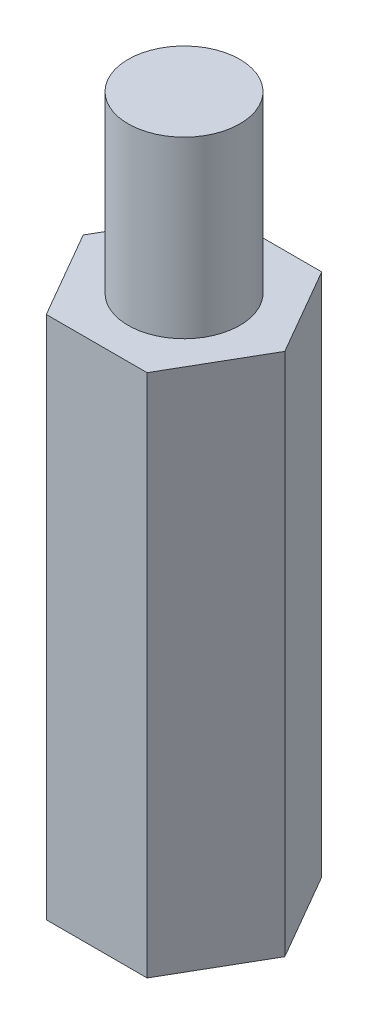
SolidWorks part; units mm, degrees
ref_plane "Front Plane" through (0, 0, 0) normal (0, 0, 1) x (1, 0, 0)
ref_plane "Top Plane" through (0, 0, 0) normal (0, 1, 0) x (1, 0, 0)
ref_plane "Right Plane" through (0, 0, 0) normal (1, 0, 0) x (0, 0, -1)
sketch "Sketch1" plane through (0, 0, 0) normal (0, 1, 0) x (1, 0, 0)
  line L0 (0, 52.3008) -> (0, -73.4946) construction
  line L1 (-96.1697, 0) -> (114.4009, 0) construction
  line L2 (-1.3748, 2.3812) -> (1.3748, 2.3812)
  line L3 (1.3748, 2.3812) -> (2.7496, 0)
  line L4 (2.7496, 0) -> (1.3748, -2.3813)
  line L5 (1.3748, -2.3813) -> (-1.3748, -2.3813)
  line L6 (-1.3748, -2.3813) -> (-2.7496, 0)
  line L7 (-2.7496, 0) -> (-1.3748, 2.3812)
  line L8 (-2.4183, 4.1886) -> (84.832, -146.9333) construction
  line L9 (45.1979, 78.2851) -> (-38.8958, -67.3694) construction
  point P16 (-14.3245, 25.8655)
  point P17 (24.412, 29.7397)
  point P18 (44.2107, 0)
  point P19 (22.2527, -37.488)
  point P20 (-16.5612, -41.2279)
  point P21 (-40.6915, 0)
  dimension "D1" = 60
  dimension "D2" = 4.7625
extrude "Boss-Extrude1" add sketch "Sketch1" along normal blind 14.3002
sketch "Sketch2" plane through (0, 14.3002, 0) normal (0, 1, 0) x (1, 0, 0)
  circle A0 centre (0, 0) radius 1.524
  dimension "D1" = 3.048
extrude "Boss-Extrude2" add sketch "Sketch2" along normal blind 4.7625
sketch "Sketch3" plane through (0, 0, 0) normal (0, -1, 0) x (1, 0, 0)
  circle A0 centre (0, 0) radius 0.7937
  dimension "D1" = 1.5875
extrude "Cut-Extrude1" cut sketch "Sketch3" against normal blind 4.7625
